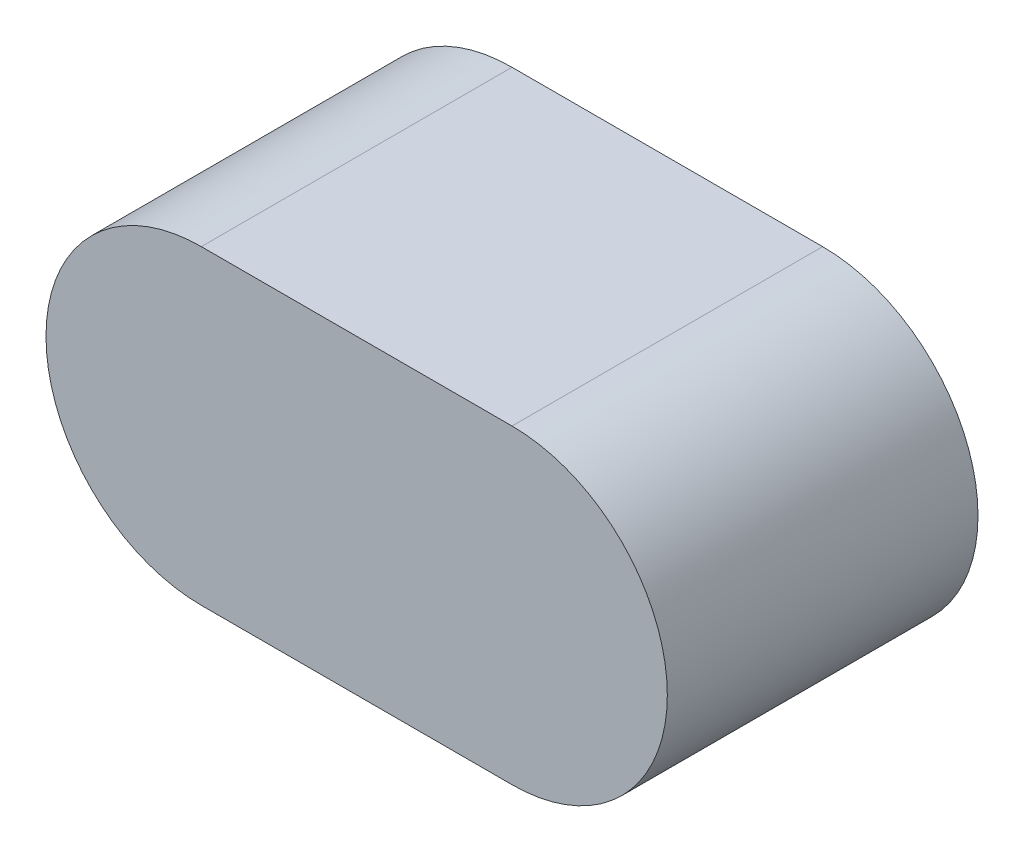
SolidWorks part; units mm, degrees
ref_plane "前视基准面" through (0, 0, 0) normal (0, 0, 1) x (1, 0, 0)
ref_plane "上视基准面" through (0, 0, 0) normal (0, 1, 0) x (1, 0, 0)
ref_plane "右视基准面" through (0, 0, 0) normal (1, 0, 0) x (0, 0, -1)
other "Configuration Table"
sketch "草图1" plane through (0, 0, 0) normal (0, 0, 1) x (1, 0, 0)
  line L0 (-50.7979, 48.8298) -> (-45.7979, 48.8298) construction
  line L1 (-50.7979, 51.3298) -> (-45.7979, 51.3298)
  line L2 (-50.7979, 46.3298) -> (-45.7979, 46.3298)
  arc A0 (-50.7979, 51.3298) -> (-50.7979, 46.3298) centre (-50.7979, 48.8298) ccw
  arc A1 (-45.7979, 46.3298) -> (-45.7979, 51.3298) centre (-45.7979, 48.8298) ccw
  point P2 (-48.2979, 48.8298)
  dimension "D1" = 2.5
  dimension "D2" = 5
extrude "凸台-拉伸1" add sketch "草图1" along normal blind 5
